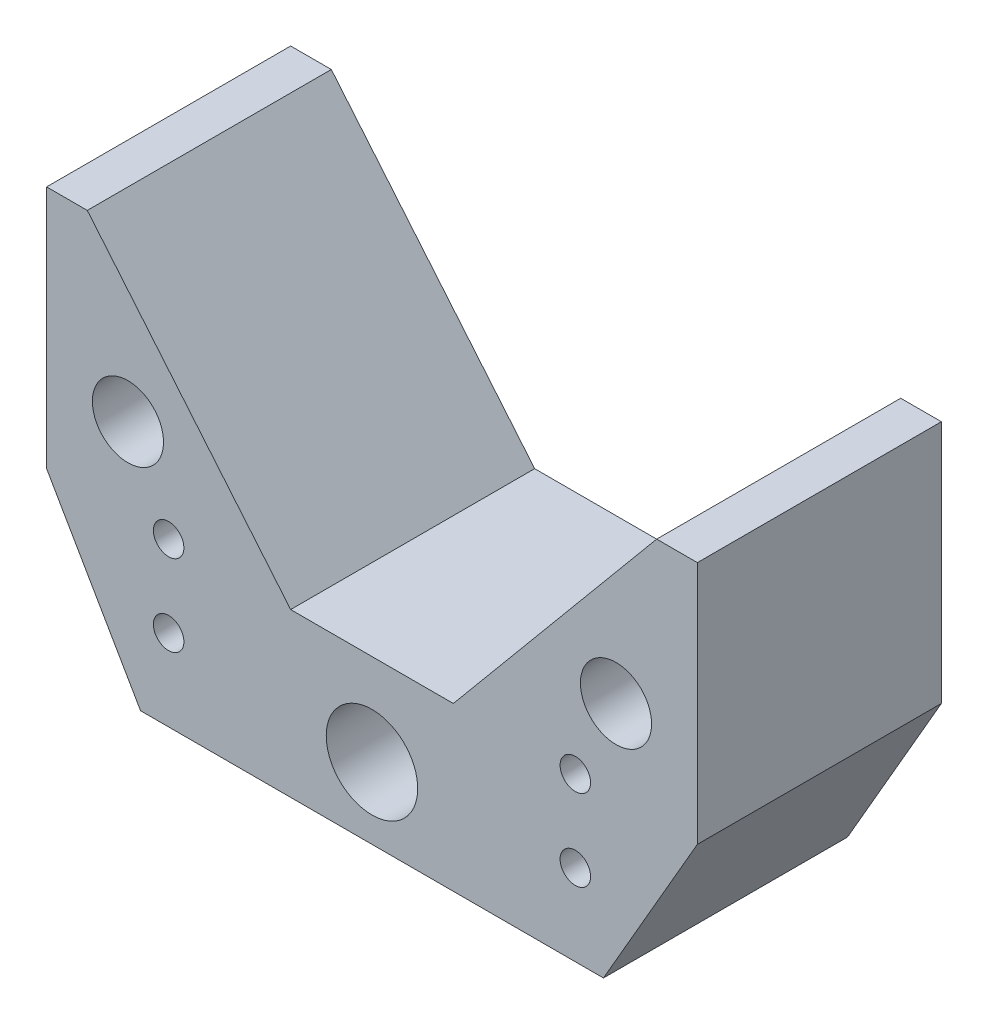
SolidWorks part; units mm, degrees
ref_plane "Front Plane" through (0, 0, 0) normal (0, 0, 1) x (1, 0, 0)
ref_plane "Top Plane" through (0, 0, 0) normal (0, 1, 0) x (1, 0, 0)
ref_plane "Right Plane" through (0, 0, 0) normal (1, 0, 0) x (0, 0, -1)
sketch "Sketch1" plane through (0, 0, 0) normal (0, 0, 1) x (1, 0, 0)
  line L7 (-72.2706, 0) -> (72.2706, 0)
  line L8 (72.2706, 0) -> (101.6, 50.8)
  line L9 (101.6, 50.8) -> (101.6, 127)
  line L10 (101.6, 127) -> (88.9, 127)
  line L11 (88.9, 127) -> (25.4, 50.8)
  line L12 (25.4, 50.8) -> (-25.4, 50.8)
  line L29 (-88.9, 127) -> (-25.4, 50.8)
  line L30 (-101.6, 127) -> (-88.9, 127)
  line L31 (-101.6, 50.8) -> (-101.6, 127)
  line L32 (-72.2706, 0) -> (-101.6, 50.8)
  circle A0 centre (76.2, 76.2) radius 11.1125
  circle A1 centre (63.5, 50.8) radius 4.7625
  circle A2 centre (63.5, 25.4) radius 4.7625
  circle A7 centre (0, 22.225) radius 14.2875
  circle A11 centre (-63.5, 25.4) radius 4.7625
  circle A12 centre (-63.5, 50.8) radius 4.7625
  circle A13 centre (-76.2, 76.2) radius 11.1125
  point P0 (0, 0)
  dimension "D7" = 22.225
  dimension "D8" = 25.4
  dimension "D10" = 9.525
  dimension "D11" = 9.525
  dimension "D12" = 12.7
  dimension "D13" = 12.7
  dimension "D14" = 25.4
  dimension "D15" = 25.4
  dimension "D16" = 28.575
  dimension "D18" = 28.575
  dimension "D2" = 120
  dimension "D3" = 50.8
  dimension "D4" = 76.2
  dimension "D5" = 12.7
  dimension "D9" = 25.4
extrude "Boss-Extrude4" add sketch "Sketch1" along normal blind 76.2 contours A13 | A12 | A7 | A0 | L29 L12 L11 L10 L9 L8 L7 L32 L31 L30 | A11 | A2 | A1
